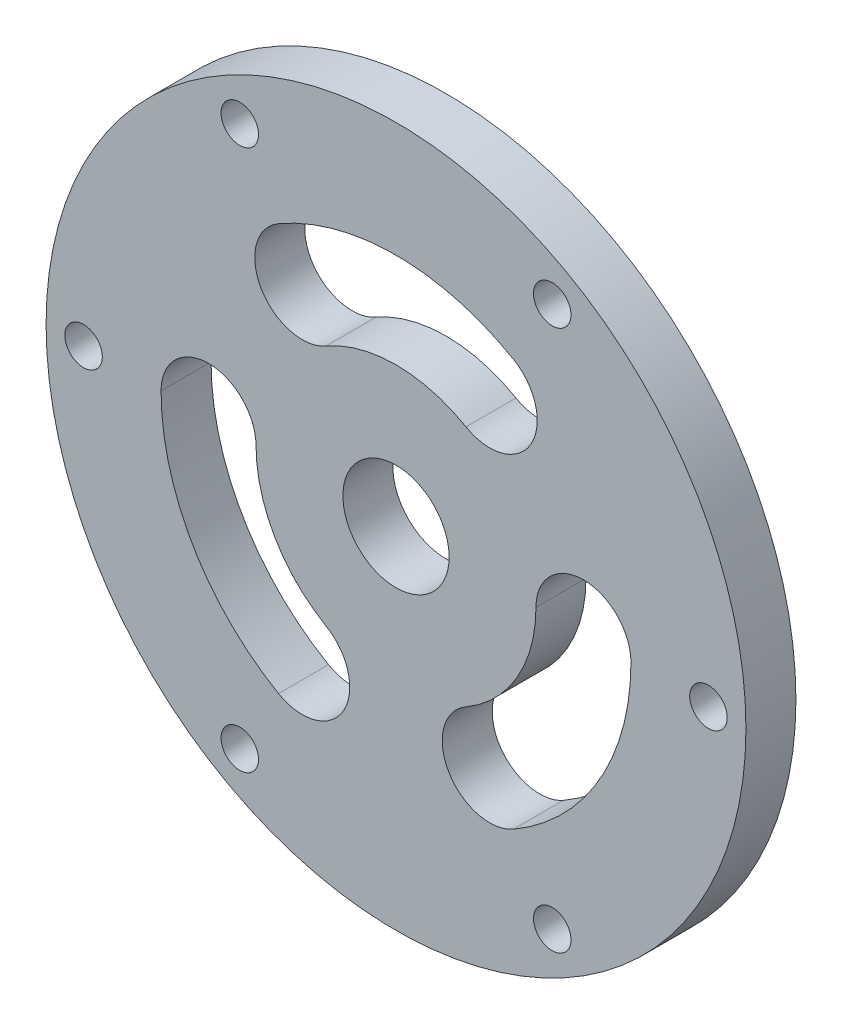
SolidWorks part; units mm, degrees
ref_plane "前视基准面" through (0, 0, 0) normal (0, 0, 1) x (1, 0, 0)
ref_plane "上视基准面" through (0, 0, 0) normal (0, 1, 0) x (1, 0, 0)
ref_plane "右视基准面" through (0, 0, 0) normal (1, 0, 0) x (0, 0, -1)
sketch "草图1" plane through (0, 0, 0) normal (0, 0, 1) x (1, 0, 0)
  line L5 (14, 24.2487) -> (12.5, 21.6506) construction
  circle A0 centre (0, 0) radius 15 construction
  arc A1 (-11.2, 0) -> (-5.6, -9.6995) centre (0, 0) ccw
  circle A11 centre (0, 0) radius 4.25
  arc A17 (11.2, 0) -> (18.8, 0) centre (15, 0) cw
  arc A18 (5.6, -9.6995) -> (9.4, -16.2813) centre (7.5, -12.9904) ccw
  arc A21 (5.6, -9.6995) -> (11.2, 0) centre (0, 0) ccw
  arc A22 (9.4, -16.2813) -> (18.8, 0) centre (0, 0) ccw
  circle A31 centre (0, 0) radius 35.5 construction
  circle A32 centre (0, 0) radius 25 construction
  circle A50 centre (0, 0) radius 28
  circle A54 centre (12.5, 21.6506) radius 1.5
  circle A55 centre (25, 0) radius 1.5
  circle A56 centre (12.5, -21.6506) radius 1.5
  circle A57 centre (-12.5, -21.6506) radius 1.5
  circle A58 centre (-25, 0) radius 1.5
  circle A59 centre (-12.5, 21.6506) radius 1.5
  arc A60 (-18.8, 0) -> (-9.4, -16.2813) centre (0, 0) ccw
  arc A61 (-5.6, -9.6995) -> (-9.4, -16.2813) centre (-7.5, -12.9904) cw
  arc A62 (-11.2, 0) -> (-18.8, 0) centre (-15, 0) ccw
  arc A63 (5.6, 9.6995) -> (-5.6, 9.6995) centre (0, 0) ccw
  arc A64 (9.4, 16.2813) -> (-9.4, 16.2813) centre (0, 0) ccw
  arc A65 (-5.6, 9.6995) -> (-9.4, 16.2813) centre (-7.5, 12.9904) cw
  arc A66 (5.6, 9.6995) -> (9.4, 16.2813) centre (7.5, 12.9904) ccw
  dimension "D1" = 3
  dimension "D2" = 6
extrude "凸台-拉伸1" add sketch "草图1" along normal blind 4
sketch "草图2" plane through (0, 0, 4) normal (0, 0, 1) x (1, 0, 0)
  circle A0 centre (0, 0) radius 5
sketch "草图3" plane through (0, 0, 0) normal (0, 0, -1) x (-1, 0, 0)
  circle A0 centre (0, 0.2466) radius 5
